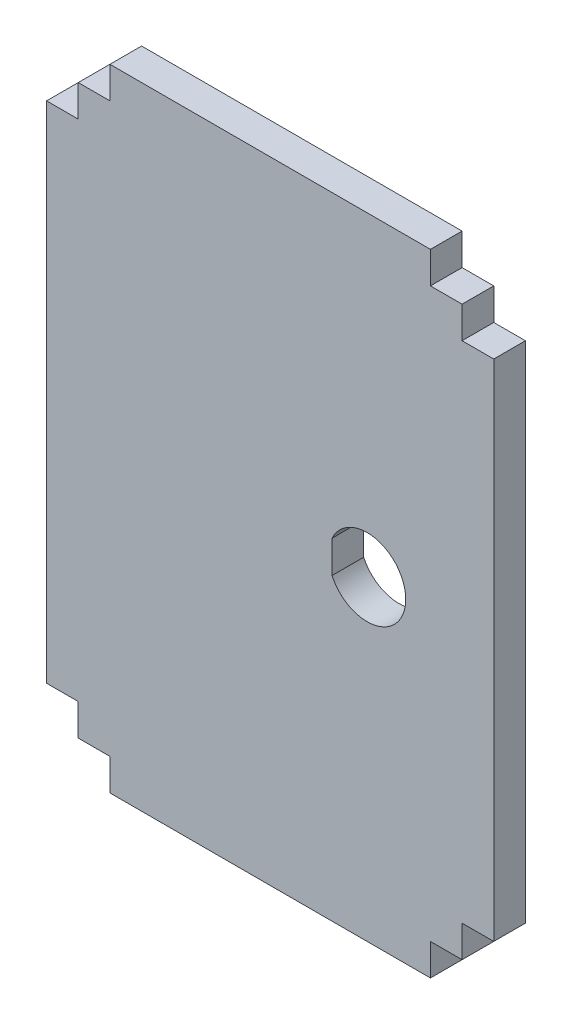
SolidWorks part; units mm, degrees
material "Acrylic (Medium-high impact)"
ref_plane "Front Plane" through (0, 0, 0) normal (0, 0, 1) x (1, 0, 0)
ref_plane "Top Plane" through (0, 0, 0) normal (0, 1, 0) x (1, 0, 0)
ref_plane "Right Plane" through (0, 0, 0) normal (1, 0, 0) x (0, 0, -1)
sketch "Sketch1" plane through (0, 0, 0) normal (0, 0, 1) x (1, 0, 0)
  line L24 (-30.2333, -35.1837) -> (-23.8833, -35.1837)
  line L25 (-30.2333, -28.8337) -> (-30.2333, -35.1837)
  line L26 (-36.5833, -28.8337) -> (-30.2333, -28.8337)
  line L27 (-36.5833, 72.3345) -> (-36.5833, -28.8337)
  line L28 (-30.2333, 72.3345) -> (-36.5833, 72.3345)
  line L29 (-30.2333, 78.6845) -> (-30.2333, 72.3345)
  line L30 (-23.8833, 78.6845) -> (-30.2333, 78.6845)
  line L31 (-23.8833, 85.0345) -> (-23.8833, 78.6845)
  line L32 (40.4041, 85.0345) -> (-23.8833, 85.0345)
  line L33 (40.4041, 78.6845) -> (40.4041, 85.0345)
  line L34 (46.7541, 78.6845) -> (40.4041, 78.6845)
  line L35 (46.7541, 72.3345) -> (46.7541, 78.6845)
  line L36 (53.1041, 72.3345) -> (46.7541, 72.3345)
  line L37 (53.1041, 28.6973) -> (53.1041, 72.3345)
  line L38 (62.3624, 28.6973) -> (53.1041, 28.6973)
  line L39 (75.0624, -16.1337) -> (75.0624, 15.9973)
  line L40 (46.7541, -28.8337) -> (62.3624, -28.8337)
  line L41 (46.7541, -35.1837) -> (46.7541, -28.8337)
  line L42 (40.4041, -35.1837) -> (46.7541, -35.1837)
  line L43 (40.4041, -41.5337) -> (40.4041, -35.1837)
  line L44 (-23.8833, -41.5337) -> (40.4041, -41.5337)
  line L45 (-23.8833, -35.1837) -> (-23.8833, -41.5337)
  line L46 (-30.2333, -35.1837) -> (-23.8833, -35.1837)
  line L47 (-30.2333, -28.8337) -> (-30.2333, -35.1837)
  line L48 (-36.5833, -28.8337) -> (-30.2333, -28.8337)
  line L49 (-36.5833, 72.3345) -> (-36.5833, -28.8337)
  line L50 (-30.2333, 72.3345) -> (-36.5833, 72.3345)
  line L51 (-30.2333, 78.6845) -> (-30.2333, 72.3345)
  line L52 (-23.8833, 78.6845) -> (-30.2333, 78.6845)
  line L53 (-23.8833, 85.0345) -> (-23.8833, 78.6845)
  line L54 (40.4041, 85.0345) -> (-23.8833, 85.0345)
  line L55 (40.4041, 78.6845) -> (40.4041, 85.0345)
  line L56 (46.7541, 78.6845) -> (40.4041, 78.6845)
  line L57 (46.7541, 72.3345) -> (46.7541, 78.6845)
  line L58 (53.1041, 72.3345) -> (46.7541, 72.3345)
  line L59 (53.1041, -28.8337) -> (53.1041, 72.3345)
  line L62 (46.7541, -28.8337) -> (53.1041, -28.8337)
  line L63 (46.7541, -35.1837) -> (46.7541, -28.8337)
  line L64 (40.4041, -35.1837) -> (46.7541, -35.1837)
  line L65 (40.4041, -41.5337) -> (40.4041, -35.1837)
  line L66 (-23.8833, -41.5337) -> (40.4041, -41.5337)
  line L67 (-23.8833, -35.1837) -> (-23.8833, -41.5337)
  arc A3 (75.0624, 15.9973) -> (62.3624, 28.6973) centre (62.3624, 15.9973) ccw
  arc A5 (62.3624, -28.8337) -> (75.0624, -16.1337) centre (62.3624, -16.1337) ccw
  dimension "D1" = 0
extrude "Boss-Extrude1" add sketch "Sketch1" against normal blind 6.35
sketch "Sketch2" plane through (0, 0, -6.35) normal (0, 0, -1) x (-1, 0, 0)
  line L0 (-20.6683, 24.9929) -> (-20.6683, 18.508)
  line L1 (-27.7041, 85.0345) -> (-27.7041, 21.7504) construction
  line L2 (-27.7041, 21.7504) -> (-27.7041, -41.5337) construction
  line L3 (-46.7541, -41.5337) -> (-46.7541, 85.0345) construction
  line L4 (-40.4041, 85.0345) -> (23.8833, 85.0345) construction
  line L5 (23.8833, -41.5337) -> (-40.4041, -41.5337) construction
  arc A0 (-20.6683, 24.9929) -> (-20.6683, 18.508) centre (-27.7041, 21.7504) ccw
  dimension "D1" = 15.494
  dimension "D2" = 6.4849
  dimension "D3" = 19.05
extrude "Cut-Extrude1" cut sketch "Sketch2" against normal through all
